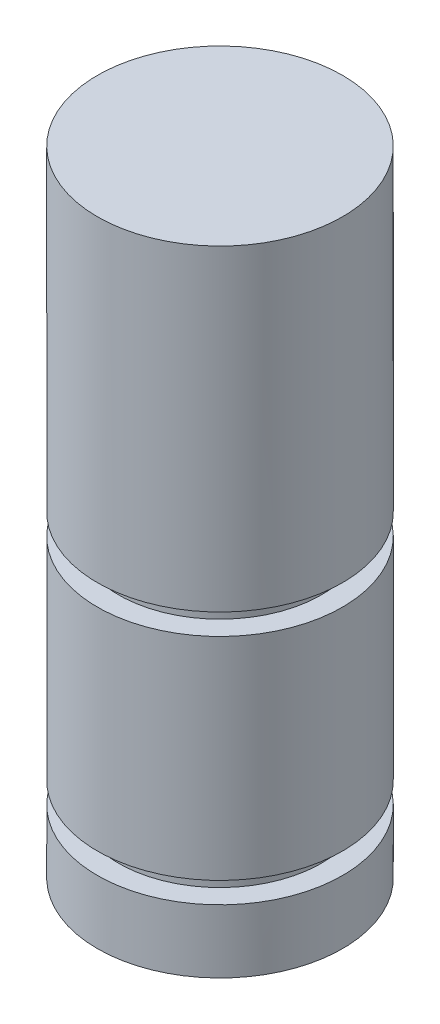
SolidWorks part; units mm, degrees
ref_plane "Front Plane" through (0, 0, 0) normal (0, 0, 1) x (1, 0, 0)
ref_plane "Top Plane" through (0, 0, 0) normal (0, 1, 0) x (1, 0, 0)
ref_plane "Right Plane" through (0, 0, 0) normal (1, 0, 0) x (0, 0, -1)
sketch "Sketch1" plane through (0, 0, 0) normal (0, 1, 0) x (1, 0, 0)
  circle A0 centre (0, 0) radius 5.8
  dimension "D1" = 11.6
extrude "Boss-Extrude1" add sketch "Sketch1" along normal blind 30 contours A0
sketch "Sketch2" plane through (0, 0, 0) normal (0, -1, 0) x (1, 0, 0)
  circle A0 centre (0, 0) radius 2.1
  dimension "D1" = 4.2
extrude "Cut-Extrude1" cut sketch "Sketch2" against normal blind 10
ref_plane "Plane1" through (0, 14, 0) normal (0, -1, 0) x (-1, 0, 0)
ref_plane "Plane2" through (0, 4, 0) normal (0, -1, 0) x (-1, 0, 0)
sketch "Sketch3" plane through (0, 14, 0) normal (0, -1, 0) x (-1, 0, 0)
  circle A0 centre (0, 0) radius 5.8 construction
  circle A1 centre (0, 0) radius 5.8
  circle A2 centre (0, 0) radius 4.8
  dimension "D1" = 1
extrude "Cut-Extrude2" cut sketch "Sketch3" against normal blind 1
sketch "Sketch4" plane through (0, 4, 0) normal (0, -1, 0) x (-1, 0, 0)
  circle A0 centre (0, 0) radius 5.8 construction
  circle A1 centre (0, 0) radius 5.8
  circle A2 centre (0, 0) radius 4.8
  dimension "D1" = 1
extrude "Cut-Extrude3" cut sketch "Sketch4" along normal blind 1
